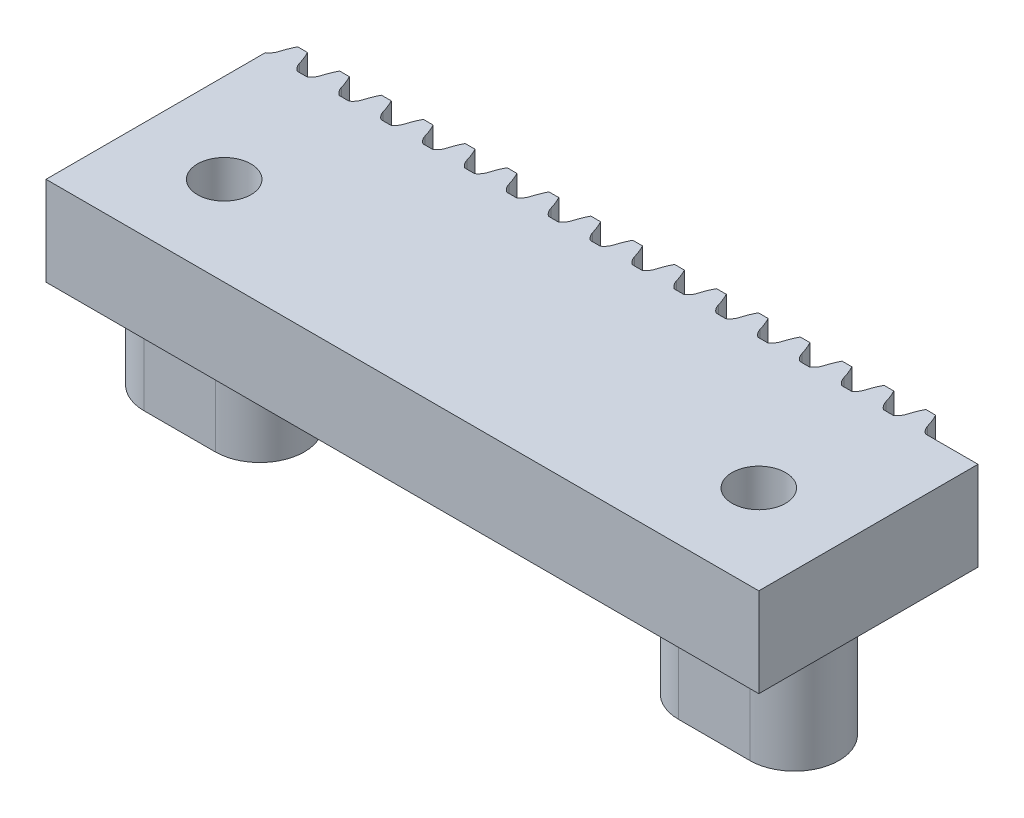
SolidWorks part; units mm, degrees
ref_plane "Front Plane" through (0, 0, 0) normal (0, 0, 1) x (1, 0, 0)
ref_plane "Top Plane" through (0, 0, 0) normal (0, 1, 0) x (1, 0, 0)
ref_plane "Right Plane" through (0, 0, 0) normal (1, 0, 0) x (0, 0, -1)
sketch "Sketch1" plane through (0, 0, 0) normal (0, 1, 0) x (1, 0, 0)
  line L0 (0, 0) -> (40, 0)
  line L1 (40, 0) -> (40, 12.3)
  line L2 (40, 13.15) -> (0, 13.15) construction
  line L3 (0, 12.3) -> (0, 0)
  line L4 (0, 12.3) -> (40, 12.3) construction
  line L5 (40, 13.5) -> (0, 13.5) construction
  line L6 (0, 12.75) -> (40, 12.75) construction
  line L7 (0.625, 13.5) -> (1.175, 13.5)
  line L8 (0.9, 13.5) -> (0.9, 12.3) construction
  line L9 (1.8, 12.3) -> (2.35, 12.3)
  line L10 (4.15, 12.3) -> (4.7, 12.3)
  line L11 (2.975, 13.5) -> (3.525, 13.5)
  line L12 (3.25, 13.5) -> (3.25, 12.3) construction
  line L13 (6.5, 12.3) -> (7.05, 12.3)
  line L14 (5.325, 13.5) -> (5.875, 13.5)
  line L15 (5.6, 13.5) -> (5.6, 12.3) construction
  line L16 (8.85, 12.3) -> (9.4, 12.3)
  line L17 (7.675, 13.5) -> (8.225, 13.5)
  line L18 (7.95, 13.5) -> (7.95, 12.3) construction
  line L19 (11.2, 12.3) -> (11.75, 12.3)
  line L20 (10.025, 13.5) -> (10.575, 13.5)
  line L21 (10.3, 13.5) -> (10.3, 12.3) construction
  line L22 (13.55, 12.3) -> (14.1, 12.3)
  line L23 (12.375, 13.5) -> (12.925, 13.5)
  line L24 (12.65, 13.5) -> (12.65, 12.3) construction
  line L25 (15.9, 12.3) -> (16.45, 12.3)
  line L26 (14.725, 13.5) -> (15.275, 13.5)
  line L27 (15, 13.5) -> (15, 12.3) construction
  line L28 (18.25, 12.3) -> (18.8, 12.3)
  line L29 (17.075, 13.5) -> (17.625, 13.5)
  line L30 (17.35, 13.5) -> (17.35, 12.3) construction
  line L31 (20.6, 12.3) -> (21.15, 12.3)
  line L32 (19.425, 13.5) -> (19.975, 13.5)
  line L33 (19.7, 13.5) -> (19.7, 12.3) construction
  line L34 (22.95, 12.3) -> (23.5, 12.3)
  line L35 (21.775, 13.5) -> (22.325, 13.5)
  line L36 (22.05, 13.5) -> (22.05, 12.3) construction
  line L37 (25.3, 12.3) -> (25.85, 12.3)
  line L38 (24.125, 13.5) -> (24.675, 13.5)
  line L39 (24.4, 13.5) -> (24.4, 12.3) construction
  line L40 (27.65, 12.3) -> (28.2, 12.3)
  line L41 (26.475, 13.5) -> (27.025, 13.5)
  line L42 (26.75, 13.5) -> (26.75, 12.3) construction
  line L43 (30, 12.3) -> (30.55, 12.3)
  line L44 (28.825, 13.5) -> (29.375, 13.5)
  line L45 (29.1, 13.5) -> (29.1, 12.3) construction
  line L46 (32.35, 12.3) -> (32.9, 12.3)
  line L47 (31.175, 13.5) -> (31.725, 13.5)
  line L48 (31.45, 13.5) -> (31.45, 12.3) construction
  line L49 (34.7, 12.3) -> (35.25, 12.3)
  line L50 (33.525, 13.5) -> (34.075, 13.5)
  line L51 (33.8, 13.5) -> (33.8, 12.3) construction
  line L53 (35.875, 13.5) -> (36.425, 13.5)
  line L54 (36.15, 13.5) -> (36.15, 12.3) construction
  line L55 (37.05, 12.3) -> (37.6, 12.3) [skipped]
  line L56 (37.05, 12.3) -> (40, 12.3)
  arc A0 (0, 12.3) -> (0.325, 12.75) centre (-0.4614, 12.9756) ccw
  arc A1 (0.325, 12.75) -> (0.625, 13.5) centre (4.1699, 11.647) cw
  arc A2 (1.475, 12.75) -> (1.175, 13.5) centre (-2.3699, 11.647) ccw
  arc A3 (1.8, 12.3) -> (1.475, 12.75) centre (2.2614, 12.9756) cw
  arc A4 (4.15, 12.3) -> (3.825, 12.75) centre (4.6114, 12.9756) cw
  arc A5 (3.825, 12.75) -> (3.525, 13.5) centre (-0.0199, 11.647) ccw
  arc A6 (2.675, 12.75) -> (2.975, 13.5) centre (6.5199, 11.647) cw
  arc A7 (2.35, 12.3) -> (2.675, 12.75) centre (1.8886, 12.9756) ccw
  arc A8 (6.5, 12.3) -> (6.175, 12.75) centre (6.9614, 12.9756) cw
  arc A9 (6.175, 12.75) -> (5.875, 13.5) centre (2.3301, 11.647) ccw
  arc A10 (5.025, 12.75) -> (5.325, 13.5) centre (8.8699, 11.647) cw
  arc A11 (4.7, 12.3) -> (5.025, 12.75) centre (4.2386, 12.9756) ccw
  arc A12 (8.85, 12.3) -> (8.525, 12.75) centre (9.3114, 12.9756) cw
  arc A13 (8.525, 12.75) -> (8.225, 13.5) centre (4.6801, 11.647) ccw
  arc A14 (7.375, 12.75) -> (7.675, 13.5) centre (11.2199, 11.647) cw
  arc A15 (7.05, 12.3) -> (7.375, 12.75) centre (6.5886, 12.9756) ccw
  arc A16 (11.2, 12.3) -> (10.875, 12.75) centre (11.6614, 12.9756) cw
  arc A17 (10.875, 12.75) -> (10.575, 13.5) centre (7.0301, 11.647) ccw
  arc A18 (9.725, 12.75) -> (10.025, 13.5) centre (13.5699, 11.647) cw
  arc A19 (9.4, 12.3) -> (9.725, 12.75) centre (8.9386, 12.9756) ccw
  arc A20 (13.55, 12.3) -> (13.225, 12.75) centre (14.0114, 12.9756) cw
  arc A21 (13.225, 12.75) -> (12.925, 13.5) centre (9.3801, 11.647) ccw
  arc A22 (12.075, 12.75) -> (12.375, 13.5) centre (15.9199, 11.647) cw
  arc A23 (11.75, 12.3) -> (12.075, 12.75) centre (11.2886, 12.9756) ccw
  arc A24 (15.9, 12.3) -> (15.575, 12.75) centre (16.3614, 12.9756) cw
  arc A25 (15.575, 12.75) -> (15.275, 13.5) centre (11.7301, 11.647) ccw
  arc A26 (14.425, 12.75) -> (14.725, 13.5) centre (18.2699, 11.647) cw
  arc A27 (14.1, 12.3) -> (14.425, 12.75) centre (13.6386, 12.9756) ccw
  arc A28 (18.25, 12.3) -> (17.925, 12.75) centre (18.7114, 12.9756) cw
  arc A29 (17.925, 12.75) -> (17.625, 13.5) centre (14.0801, 11.647) ccw
  arc A30 (16.775, 12.75) -> (17.075, 13.5) centre (20.6199, 11.647) cw
  arc A31 (16.45, 12.3) -> (16.775, 12.75) centre (15.9886, 12.9756) ccw
  arc A32 (20.6, 12.3) -> (20.275, 12.75) centre (21.0614, 12.9756) cw
  arc A33 (20.275, 12.75) -> (19.975, 13.5) centre (16.4301, 11.647) ccw
  arc A34 (19.125, 12.75) -> (19.425, 13.5) centre (22.9699, 11.647) cw
  arc A35 (18.8, 12.3) -> (19.125, 12.75) centre (18.3386, 12.9756) ccw
  arc A36 (22.95, 12.3) -> (22.625, 12.75) centre (23.4114, 12.9756) cw
  arc A37 (22.625, 12.75) -> (22.325, 13.5) centre (18.7801, 11.647) ccw
  arc A38 (21.475, 12.75) -> (21.775, 13.5) centre (25.3199, 11.647) cw
  arc A39 (21.15, 12.3) -> (21.475, 12.75) centre (20.6886, 12.9756) ccw
  arc A40 (25.3, 12.3) -> (24.975, 12.75) centre (25.7614, 12.9756) cw
  arc A41 (24.975, 12.75) -> (24.675, 13.5) centre (21.1301, 11.647) ccw
  arc A42 (23.825, 12.75) -> (24.125, 13.5) centre (27.6699, 11.647) cw
  arc A43 (23.5, 12.3) -> (23.825, 12.75) centre (23.0386, 12.9756) ccw
  arc A44 (27.65, 12.3) -> (27.325, 12.75) centre (28.1114, 12.9756) cw
  arc A45 (27.325, 12.75) -> (27.025, 13.5) centre (23.4801, 11.647) ccw
  arc A46 (26.175, 12.75) -> (26.475, 13.5) centre (30.0199, 11.647) cw
  arc A47 (25.85, 12.3) -> (26.175, 12.75) centre (25.3886, 12.9756) ccw
  arc A48 (30, 12.3) -> (29.675, 12.75) centre (30.4614, 12.9756) cw
  arc A49 (29.675, 12.75) -> (29.375, 13.5) centre (25.8301, 11.647) ccw
  arc A50 (28.525, 12.75) -> (28.825, 13.5) centre (32.3699, 11.647) cw
  arc A51 (28.2, 12.3) -> (28.525, 12.75) centre (27.7386, 12.9756) ccw
  arc A52 (32.35, 12.3) -> (32.025, 12.75) centre (32.8114, 12.9756) cw
  arc A53 (32.025, 12.75) -> (31.725, 13.5) centre (28.1801, 11.647) ccw
  arc A54 (30.875, 12.75) -> (31.175, 13.5) centre (34.7199, 11.647) cw
  arc A55 (30.55, 12.3) -> (30.875, 12.75) centre (30.0886, 12.9756) ccw
  arc A56 (34.7, 12.3) -> (34.375, 12.75) centre (35.1614, 12.9756) cw
  arc A57 (34.375, 12.75) -> (34.075, 13.5) centre (30.5301, 11.647) ccw
  arc A58 (33.225, 12.75) -> (33.525, 13.5) centre (37.0699, 11.647) cw
  arc A59 (32.9, 12.3) -> (33.225, 12.75) centre (32.4386, 12.9756) ccw
  arc A60 (37.05, 12.3) -> (36.725, 12.75) centre (37.5114, 12.9756) cw
  arc A61 (36.725, 12.75) -> (36.425, 13.5) centre (32.8801, 11.647) ccw
  arc A62 (35.575, 12.75) -> (35.875, 13.5) centre (39.4199, 11.647) cw
  arc A63 (35.25, 12.3) -> (35.575, 12.75) centre (34.7886, 12.9756) ccw
  point P22 (0, 0)
  point P23 (0, 0)
  point P36 (1.1054, 10.5152)
  point P50 (0, 0)
  point P63 (37.8, 9.74)
  dimension "D11" = 4
  dimension "D2" = 40
  dimension "D3" = 0.35
  dimension "D4" = 0.4
  dimension "D5" = 0.45
  dimension "D6" = 0.55
  dimension "D7" = 1.15
  dimension "D8" = 1.8
  dimension "D10" = 1.2
  dimension "D12" = 13.5
  dimension "D9" = 16
extrude "Boss-Extrude1" add sketch "Sketch1" along normal blind 5
sketch "Sketch2" plane through (0, 0, 0) normal (0, -1, 0) x (1, 0, 0)
  line L0 (7, -7.5) -> (3, -7.5)
  line L1 (3, -2.5) -> (7, -2.5)
  line L2 (0, 0) -> (40, 0) construction
  line L3 (37, -7.5) -> (33, -7.5)
  line L4 (33, -2.5) -> (37, -2.5)
  line L5 (3, -5) -> (0, -5) construction
  line L6 (0, -12.3) -> (0, 0) construction
  line L7 (37, -5) -> (40, -5) construction
  line L8 (40, 0) -> (40, -12.3) construction
  arc A0 (3, -7.5) -> (3, -2.5) centre (3, -5) cw
  arc A1 (7, -2.5) -> (7, -7.5) centre (7, -5) cw
  circle A2 centre (5, -5) radius 1.5
  arc A3 (33, -7.5) -> (33, -2.5) centre (33, -5) cw
  arc A4 (37, -2.5) -> (37, -7.5) centre (37, -5) cw
  circle A5 centre (35, -5) radius 1.5
  point P11 (5, -7.5)
  point P20 (35, -7.5)
  dimension "D1" = 3
  dimension "D2" = 5
  dimension "D3" = 2.5
  dimension "D4" = 4
  dimension "D6" = 30
  dimension "D5" = 2
extrude "Boss-Extrude2" add sketch "Sketch2" along normal blind 6
sketch "Sketch3" plane through (0, 0, 0) normal (0, -1, 0) x (1, 0, 0)
  circle A0 centre (35, -5) radius 1.5 construction
  circle A1 centre (5, -5) radius 1.5 construction
  circle A2 centre (35, -5) radius 1.5
  circle A3 centre (5, -5) radius 1.5
extrude "Cut-Extrude1" cut sketch "Sketch3" against normal up to next
